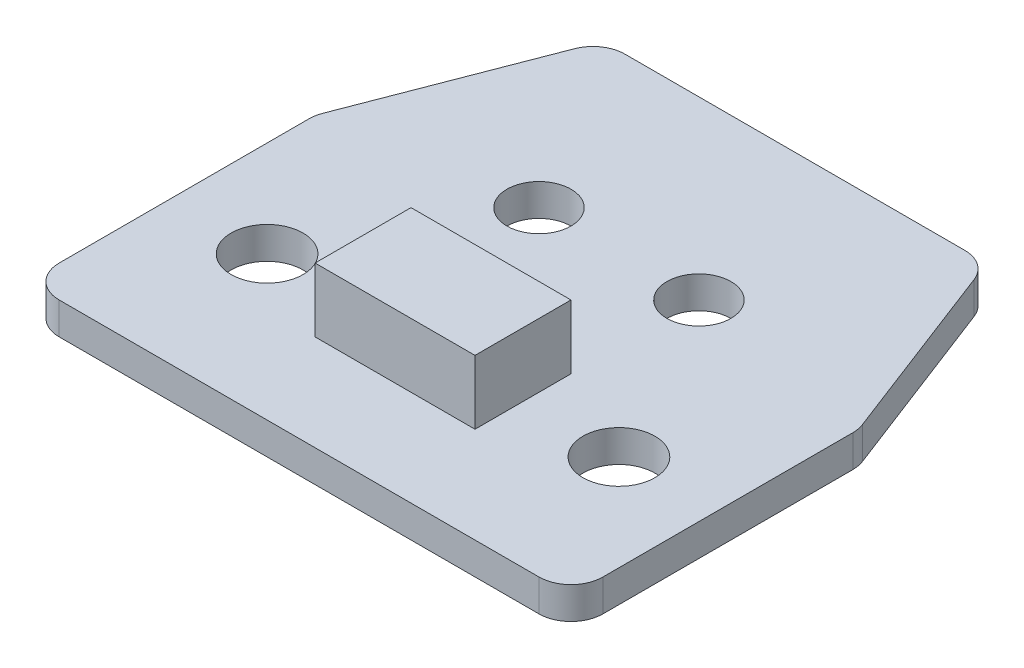
SolidWorks part; units mm, degrees
ref_plane "Спереди" through (0, 0, 0) normal (0, 0, 1) x (1, 0, 0)
ref_plane "Сверху" through (0, 0, 0) normal (0, 1, 0) x (1, 0, 0)
ref_plane "Справа" through (0, 0, 0) normal (1, 0, 0) x (0, 0, -1)
sketch "Эскиз1" plane through (0, 0, 0) normal (0, 1, 0) x (1, 0, 0)
  line L0 (0, 18) -> (5, 31)
  line L1 (0, 0) -> (34, 0)
  line L2 (0, 0) -> (0, 31)
  line L3 (0, 31) -> (34, 31)
  line L4 (34, 0) -> (34, 31)
  line L5 (5, 31) -> (29, 31)
  line L6 (29, 31) -> (34, 18)
  circle A0 centre (6, 9) radius 2.25
  circle A1 centre (28, 9) radius 2.25
  circle A2 centre (12, 20) radius 2
  circle A3 centre (22, 20) radius 2
  dimension "D1" = 4
  dimension "D3" = 4.5
  dimension "D2" = 10
  dimension "D4" = 22
  dimension "D5" = 9
  dimension "D6" = 20
  dimension "D7" = 6
  dimension "D8" = 6
  dimension "D9" = 12
  dimension "D10" = 11
  dimension "D11" = 18
  dimension "D12" = 24
  dimension "D13" = 7
extrude "Бобышка-Вытянуть1" add sketch "Эскиз1" along normal blind 2 contours L6 L3 L0 L2 L1 L4 A3 A2 A1 A0
sketch "Эскиз2" plane through (0, 2, 0) normal (0, 1, 0) x (1, 0, 0)
  line L0 (0, 0) -> (34, 0) construction
  line L1 (12, 12) -> (22, 12)
  line L2 (12, 12) -> (12, 6)
  line L3 (12, 6) -> (22, 6)
  line L4 (22, 12) -> (22, 6)
  circle A1 centre (6, 9) radius 2.25 construction
  circle A2 centre (28, 9) radius 2.25 construction
  point P4 (12, 9)
  dimension "D3" = 6
  dimension "D1" = 6
  dimension "D2" = 9
  dimension "D4" = 6
extrude "Бобышка-Вытянуть2" add sketch "Эскиз2" along normal blind 4
fillet "Скругление1" radius 2 6 edges at (5, 1, -31) (0, 1, -18) (29, 1, -31) (34, 1, -18) (0, 1, 0) (34, 1, 0)
